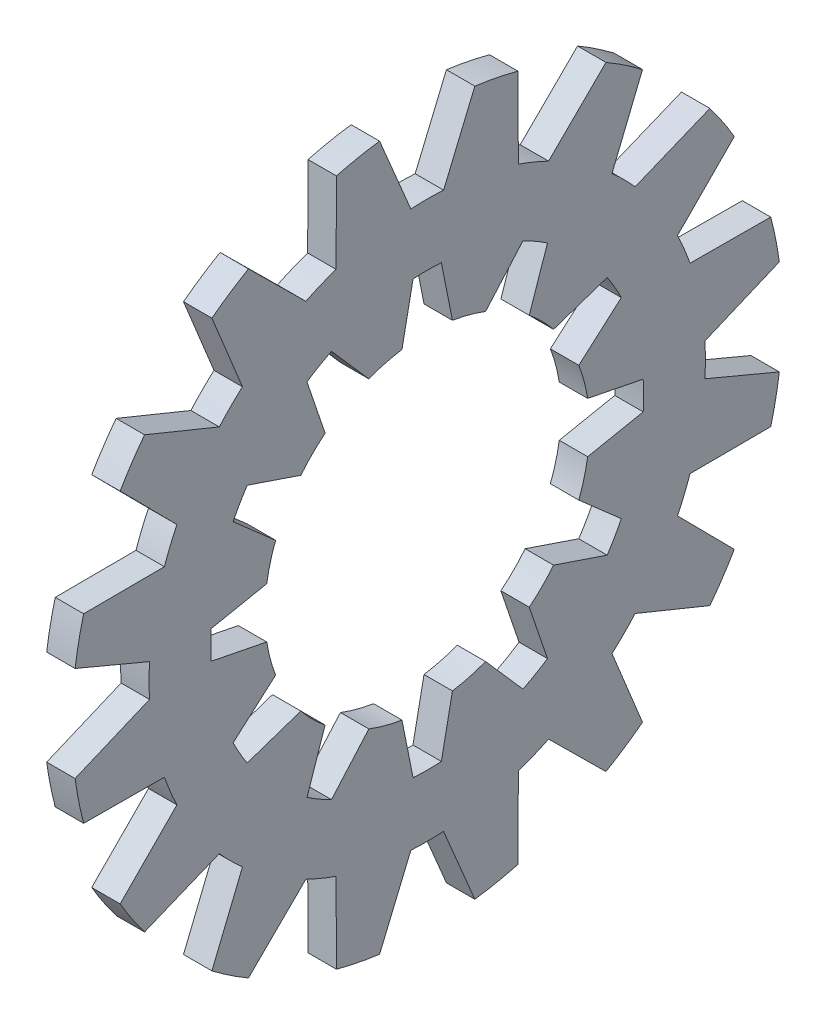
SolidWorks part; units mm, degrees
ref_plane "Plane1" through (0, 0, 0) normal (0, 0, 1) x (1, 0, 0)
ref_plane "Plane2" through (0, 0, 0) normal (0, 1, 0) x (1, 0, 0)
ref_plane "Plane3" through (0, 0, 0) normal (1, 0, 0) x (0, 0, -1)
sketch "SecSke" plane through (0, 0, 0) normal (0, 0, 1) x (1, 0, 0)
  line L0 (-34.925, 0) -> (9.525, 0) construction
  line L1 (0, 8) -> (0, 17.5)
  line L2 (0, 17.5) -> (-1.4, 17.5)
  line L3 (-1.4, 17.5) -> (-1.4, 8)
  line L4 (-1.4, 8) -> (0, 8)
  dimension "Thickness" = 1.4
  dimension "Inside_dia" = 16
  dimension "Outside_dia" = 35
revolve "Body" add sketch "SecSke" angle 360 about L0
sketch "ExtCutSke" plane through (0, 0, 0) normal (1, 0, 0) x (0, 0, -1)
  line L0 (0, 0) -> (0, 18.375) construction
  line L1 (-2.6962, 18.1761) -> (-0.8065, 13.6762)
  line L2 (2.6962, 18.1761) -> (0.8065, 13.6762)
  arc A0 (2.6962, 18.1761) -> (-2.6962, 18.1761) centre (0, 0) ccw
  arc A1 (0.8065, 13.6762) -> (-0.8065, 13.6762) centre (0, 0) ccw
  dimension "Cut_dia" = 27.4
  dimension "Clr_dia" = 36.75
  dimension "Cut_ang" = 6.75
  dimension "Clr_ang" = 16.875
extrude "ExtCut" cut sketch "ExtCutSke" against normal through all
pattern_circular "ExtCuts" count 16 every 22.5 about axis through (-34.925, 0, 0) along (1, 0, 0) of "ExtCut"
sketch "IntCutSke" plane through (0, 0, 0) normal (1, 0, 0) x (0, 0, -1)
  line L0 (-0.6972, 10.6372) -> (-1.3263, 7.4834)
  line L1 (0.6972, 10.6372) -> (1.3263, 7.4834)
  line L2 (0, 0) -> (0, 10.66) construction
  arc A0 (1.3263, 7.4834) -> (-1.3263, 7.4834) centre (0, 0) ccw
  arc A1 (0.6972, 10.6372) -> (-0.6972, 10.6372) centre (0, 0) ccw
  dimension "cut_dia" = 21.32
  dimension "Clr_dia" = 15.2
  dimension "Clr_ang" = 20.1
  dimension "Cut_ang" = 7.5
extrude "IntCut" cut sketch "IntCutSke" against normal through all
pattern_circular "IntCuts" count 12 every 30 about axis through (-34.925, 0, 0) along (1, 0, 0) of "IntCut"
equation "' \"Inside_dia@SecSke\" = 16"
equation "' \"Outside_dia@SecSke\" = 35"
equation "' \"Thickness@SecSke\" = 1.4"
equation "' \"Count@ExtCuts\" = 16"
equation "' \"Count@IntCuts\" = 12"
equation "' \"Inside_dia@SecSke\" = 10.5"
equation "' \"Outside_dia@SecSke\" = 26"
equation "' \"Thickness@SecSke\" = 1"
equation "' \"Count@ExtCuts\" = 14"
equation "' \"Count@IntCuts\" = 9"
equation "' \"Inside_dia@SecSke\" = 6.4"
equation "' \"Outside_dia@SecSke\" = 17.5"
equation "' \"Thickness@SecSke\" = 0.8"
equation "' \"Count@ExtCuts\" = 12"
equation "' \"Inside_dia@SecSke\" = 4.3"
equation "' \"Outside_dia@SecSke\" = 15"
equation "' \"Thickness@SecSke\" = 0.6"
equation "' \"Count@IntCuts\" = 8"
equation "\"Angle@ExtCuts\" = 360 / \"Count@ExtCuts\""
equation "\"Clr_dia@ExtCutSke\" =  \"Outside_dia@SecSke\" * 1.05"
equation "\"Cut_dia@ExtCutSke\" = \"Outside_dia@SecSke\" - (\"Outside_dia@SecSke\"  - \"Inside_dia@SecSke\" ) * 0.4"
equation "\"Clr_ang@ExtCutSke\" = (360 / \"Count@ExtCuts\") * 0.75"
equation "\"Cut_ang@ExtCutSke\" = (360 / \"Count@ExtCuts\") * 0.3"
equation "\"Angle@IntCuts\" = 360 / \"Count@IntCuts\""
equation "\"Clr_dia@IntCutSke\" =  \"Inside_dia@SecSke\" * 0.95"
equation "\"cut_dia@IntCutSke\" = \"Inside_dia@SecSke\" +  ( \"Outside_dia@SecSke\" - \"Inside_dia@SecSke\" )  * 0.28"
equation "\"Clr_ang@IntCutSke\" = (360 / \"Count@IntCuts\") * 0.67"
equation "\"Cut_ang@IntCutSke\" = (360 / \"Count@IntCuts\") * 0.25"
